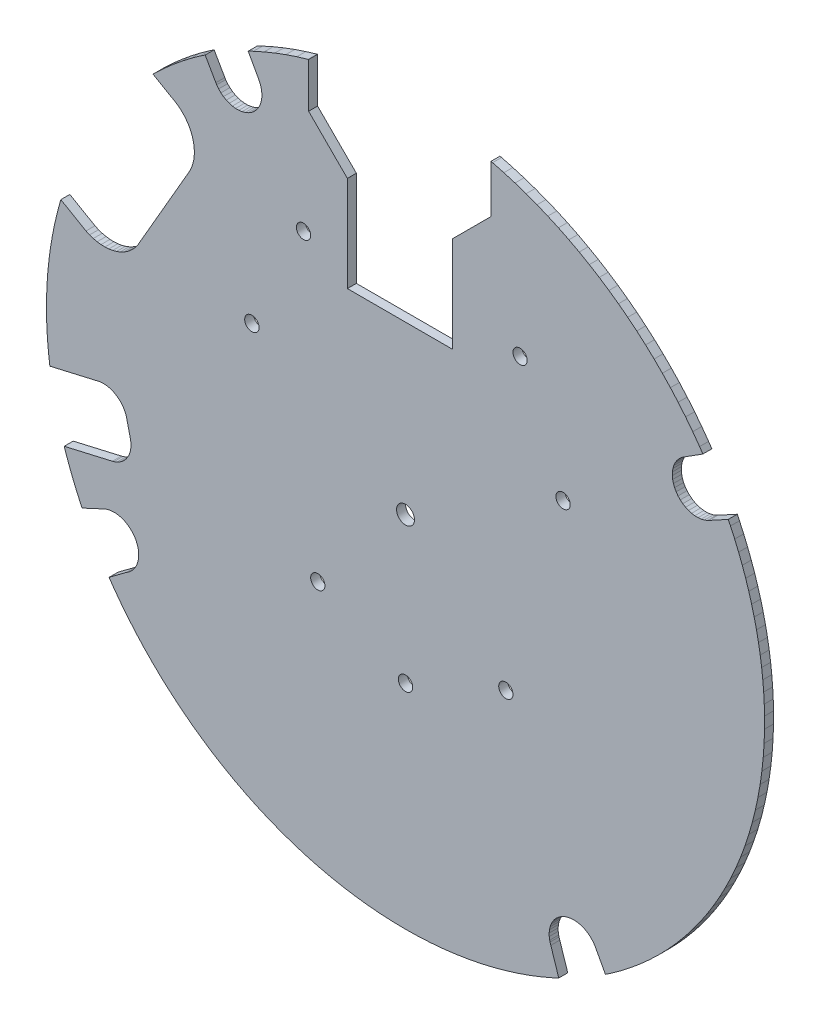
SolidWorks part; units mm, degrees
ref_plane "Płaszczyzna przednia" through (0, 0, 0) normal (0, 0, 1) x (1, 0, 0)
ref_plane "Płaszczyzna górna" through (0, 0, 0) normal (0, 1, 0) x (1, 0, 0)
ref_plane "Płaszczyzna prawa" through (0, 0, 0) normal (1, 0, 0) x (0, 0, -1)
sketch "Model" plane through (0, 0, 0) normal (0, 0, 1) x (1, 0, 0)
  line L0 (19.0436, 77.7128) -> (19.4018, 77.6295)
  line L1 (19.0436, 77.7128) -> (19.0437, 67.0537)
  line L2 (10.4176, 58.4277) -> (19.0437, 67.0537)
  line L3 (10.4176, 37.1511) -> (10.4176, 58.4277)
  line L4 (-12.9504, 37.1511) -> (10.4176, 37.1511)
  line L5 (-12.9504, 58.4177) -> (-12.9504, 37.1511)
  line L6 (-12.9603, 58.4177) -> (-12.9504, 58.4177)
  line L7 (-21.5964, 67.0537) -> (-12.9603, 58.4177)
  line L8 (-21.5964, 77.0457) -> (-21.5964, 67.0537)
  line L9 (-21.7211, 77.0127) -> (-21.5964, 77.0457)
  line L10 (-24.2112, 76.2665) -> (-21.7211, 77.0127)
  line L11 (-26.6758, 75.4398) -> (-24.2112, 76.2665)
  line L12 (-29.1122, 74.5335) -> (-26.6758, 75.4398)
  line L13 (-31.5179, 73.5485) -> (-29.1122, 74.5335)
  line L14 (-33.8903, 72.4859) -> (-31.5179, 73.5485)
  line L15 (-35.0587, 71.9164) -> (-33.8903, 72.4859)
  line L16 (-35.0587, 71.9164) -> (-32.6895, 67.6043)
  line L17 (-32.6895, 67.6043) -> (-32.532, 67.296)
  line L18 (-32.532, 67.296) -> (-32.2769, 66.6533)
  line L19 (-32.2769, 66.6533) -> (-32.1045, 65.9836)
  line L20 (-32.1045, 65.9836) -> (-32.0176, 65.2976)
  line L21 (-32.0176, 65.2976) -> (-32.0067, 64.9519)
  line L22 (-32.0185, 64.5922) -> (-32.0067, 64.9519)
  line L23 (-32.1126, 63.8789) -> (-32.0185, 64.5922)
  line L24 (-32.299, 63.184) -> (-32.1126, 63.8789)
  line L25 (-32.5747, 62.5194) -> (-32.299, 63.184)
  line L26 (-32.9348, 61.8965) -> (-32.5747, 62.5194)
  line L27 (-33.3733, 61.3261) -> (-32.9348, 61.8965)
  line L28 (-33.8826, 60.8179) -> (-33.3733, 61.3261)
  line L29 (-34.4539, 60.3805) -> (-33.8826, 60.8179)
  line L30 (-35.0775, 60.0217) -> (-34.4539, 60.3805)
  line L31 (-35.7426, 59.7473) -> (-35.0775, 60.0217)
  line L32 (-36.4379, 59.5623) -> (-35.7426, 59.7473)
  line L33 (-37.1514, 59.4697) -> (-36.4379, 59.5623)
  line L34 (-37.8709, 59.4712) -> (-37.1514, 59.4697)
  line L35 (-38.584, 59.5666) -> (-37.8709, 59.4712)
  line L36 (-39.2785, 59.7545) -> (-38.584, 59.5666)
  line L37 (-39.9425, 60.0315) -> (-39.2785, 59.7545)
  line L38 (-40.5646, 60.393) -> (-39.9425, 60.0315)
  line L39 (-41.1342, 60.8326) -> (-40.5646, 60.393)
  line L40 (-41.6414, 61.3429) -> (-41.1342, 60.8326)
  line L41 (-42.0775, 61.9151) -> (-41.6414, 61.3429)
  line L42 (-42.2666, 62.2214) -> (-42.0775, 61.9151)
  line L43 (-44.6488, 66.3808) -> (-42.2666, 62.2214)
  line L44 (-45.7359, 65.6581) -> (-44.6488, 66.3808)
  line L45 (-47.8425, 64.1394) -> (-45.7359, 65.6581)
  line L46 (-49.8986, 62.5531) -> (-47.8425, 64.1394)
  line L47 (-51.9022, 60.9009) -> (-49.8986, 62.5531)
  line L48 (-53.8511, 59.1846) -> (-51.9022, 60.9009)
  line L49 (-55.7433, 57.406) -> (-53.8511, 59.1846)
  line L50 (-56.2765, 56.8712) -> (-55.7433, 57.406)
  line L51 (-56.2765, 56.8712) -> (-51.5136, 54.1214)
  line L52 (-51.5136, 54.1214) -> (-51.1354, 53.903)
  line L53 (-51.1354, 53.903) -> (-50.4254, 53.3942)
  line L54 (-50.4254, 53.3942) -> (-49.7687, 52.8183)
  line L55 (-49.7687, 52.8183) -> (-49.1716, 52.1808)
  line L56 (-49.1716, 52.1808) -> (-48.6398, 51.4878)
  line L57 (-48.6398, 51.4878) -> (-48.1786, 50.746)
  line L58 (-48.1786, 50.746) -> (-47.7923, 49.9626)
  line L59 (-47.7923, 49.9626) -> (-47.4846, 49.1452)
  line L60 (-47.4846, 49.1452) -> (-47.2585, 48.3014)
  line L61 (-47.2585, 48.3014) -> (-47.1162, 47.4396)
  line L62 (-47.1162, 47.4396) -> (-47.0591, 46.568)
  line L63 (-47.0877, 45.695) -> (-47.0591, 46.568)
  line L64 (-47.2017, 44.829) -> (-47.0877, 45.695)
  line L65 (-47.4, 43.9784) -> (-47.2017, 44.829)
  line L66 (-47.6808, 43.1512) -> (-47.4, 43.9784)
  line L67 (-48.0413, 42.3556) -> (-47.6808, 43.1512)
  line L68 (-48.2597, 41.9774) -> (-48.0413, 42.3556)
  line L69 (-59.4357, 22.62) -> (-48.2597, 41.9774)
  line L70 (-59.654, 22.2418) -> (-59.4357, 22.62)
  line L71 (-60.1628, 21.5318) -> (-59.654, 22.2418)
  line L72 (-60.7387, 20.8751) -> (-60.1628, 21.5318)
  line L73 (-61.3762, 20.278) -> (-60.7387, 20.8751)
  line L74 (-62.0692, 19.7462) -> (-61.3762, 20.278)
  line L75 (-62.811, 19.285) -> (-62.0692, 19.7462)
  line L76 (-63.5944, 18.8986) -> (-62.811, 19.285)
  line L77 (-64.4119, 18.591) -> (-63.5944, 18.8986)
  line L78 (-65.2556, 18.3649) -> (-64.4119, 18.591)
  line L79 (-66.1174, 18.2226) -> (-65.2556, 18.3649)
  line L80 (-66.989, 18.1655) -> (-66.1174, 18.2226)
  line L81 (-67.862, 18.1941) -> (-66.989, 18.1655)
  line L82 (-68.728, 18.3081) -> (-67.862, 18.1941)
  line L83 (-69.5787, 18.5064) -> (-68.728, 18.3081)
  line L84 (-70.4058, 18.7872) -> (-69.5787, 18.5064)
  line L85 (-71.2014, 19.1477) -> (-70.4058, 18.7872)
  line L86 (-71.5796, 19.366) -> (-71.2014, 19.1477)
  line L87 (-76.8174, 22.3901) -> (-71.5796, 19.366)
  line L88 (-76.8834, 22.1744) -> (-76.8174, 22.3901)
  line L89 (-77.5625, 19.6678) -> (-76.8834, 22.1744)
  line L90 (-78.1599, 17.1405) -> (-77.5625, 19.6678)
  line L91 (-78.6749, 14.5952) -> (-78.1599, 17.1405)
  line L92 (-79.1071, 12.0345) -> (-78.6749, 14.5952)
  line L93 (-79.456, 9.4611) -> (-79.1071, 12.0345)
  line L94 (-79.7211, 6.8778) -> (-79.456, 9.4611)
  line L95 (-79.9023, 4.2872) -> (-79.7211, 6.8778)
  line L96 (-79.9994, 1.692) -> (-79.9023, 4.2872)
  line L97 (-80.0121, -0.9048) -> (-79.9994, 1.692)
  line L98 (-80.0121, -0.9048) -> (-79.9407, -3.5008)
  line L99 (-79.9407, -3.5008) -> (-79.7849, -6.093)
  line L100 (-79.7849, -6.093) -> (-79.5452, -8.6789)
  line L101 (-79.5452, -8.6789) -> (-79.257, -10.9741)
  line L102 (-79.257, -10.9741) -> (-68.5352, -8.4988)
  line L103 (-68.5352, -8.4988) -> (-68.1939, -8.42)
  line L104 (-68.1939, -8.42) -> (-67.4966, -8.3528)
  line L105 (-67.4966, -8.3528) -> (-66.7965, -8.3773)
  line L106 (-66.7965, -8.3773) -> (-66.1056, -8.4929)
  line L107 (-66.1056, -8.4929) -> (-65.4357, -8.6977)
  line L108 (-65.4357, -8.6977) -> (-64.7982, -8.9882)
  line L109 (-64.7982, -8.9882) -> (-64.2042, -9.3594)
  line L110 (-64.2042, -9.3594) -> (-63.6636, -9.805)
  line L111 (-63.6636, -9.805) -> (-63.1859, -10.3174)
  line L112 (-63.1859, -10.3174) -> (-62.7791, -10.8877)
  line L113 (-62.7791, -10.8877) -> (-62.4502, -11.5062)
  line L114 (-62.4502, -11.5062) -> (-62.2049, -12.1624)
  line L115 (-62.2049, -12.1624) -> (-62.1261, -12.5037)
  line L116 (-62.1261, -12.5037) -> (-61.3306, -15.949)
  line L117 (-61.3306, -15.949) -> (-61.2518, -16.2903)
  line L118 (-61.2518, -16.2903) -> (-61.1847, -16.9876)
  line L119 (-61.2092, -17.6877) -> (-61.1847, -16.9876)
  line L120 (-61.3248, -18.3787) -> (-61.2092, -17.6877)
  line L121 (-61.5296, -19.0486) -> (-61.3248, -18.3787)
  line L122 (-61.8201, -19.686) -> (-61.5296, -19.0486)
  line L123 (-62.1913, -20.2801) -> (-61.8201, -19.686)
  line L124 (-62.6369, -20.8206) -> (-62.1913, -20.2801)
  line L125 (-63.1492, -21.2984) -> (-62.6369, -20.8206)
  line L126 (-63.7196, -21.7052) -> (-63.1492, -21.2984)
  line L127 (-64.3381, -22.0341) -> (-63.7196, -21.7052)
  line L128 (-64.9942, -22.2794) -> (-64.3381, -22.0341)
  line L129 (-65.3355, -22.3582) -> (-64.9942, -22.2794)
  line L130 (-76.0559, -24.8332) -> (-65.3355, -22.3582)
  line L131 (-76.0559, -24.8332) -> (-75.5463, -26.3728)
  line L132 (-75.5463, -26.3728) -> (-74.6507, -28.8104)
  line L133 (-74.6507, -28.8104) -> (-73.6765, -31.2177)
  line L134 (-73.6765, -31.2177) -> (-72.6246, -33.5921)
  line L135 (-72.6246, -33.5921) -> (-72.0605, -34.7616)
  line L136 (-72.0605, -34.7616) -> (-67.6679, -32.7251)
  line L137 (-67.6679, -32.7251) -> (-67.3499, -32.5578)
  line L138 (-67.3499, -32.5578) -> (-66.6865, -32.2878)
  line L139 (-66.6865, -32.2878) -> (-65.9935, -32.1064)
  line L140 (-65.9935, -32.1064) -> (-65.2829, -32.0167)
  line L141 (-65.2829, -32.0167) -> (-64.5666, -32.0203)
  line L142 (-64.5666, -32.0203) -> (-63.8569, -32.117)
  line L143 (-63.8569, -32.117) -> (-63.1658, -32.3052)
  line L144 (-63.1658, -32.3052) -> (-62.505, -32.5818)
  line L145 (-62.505, -32.5818) -> (-61.8859, -32.942)
  line L146 (-61.8859, -32.942) -> (-61.3189, -33.3797)
  line L147 (-61.3189, -33.3797) -> (-60.8136, -33.8874)
  line L148 (-60.8136, -33.8874) -> (-60.3788, -34.4566)
  line L149 (-60.3788, -34.4566) -> (-60.0216, -35.0775)
  line L150 (-60.0216, -35.0775) -> (-59.7483, -35.7396)
  line L151 (-59.7483, -35.7396) -> (-59.5635, -36.4317)
  line L152 (-59.5635, -36.4317) -> (-59.4703, -37.1419)
  line L153 (-59.4703, -37.1419) -> (-59.4586, -37.5)
  line L154 (-59.4706, -37.8616) -> (-59.4586, -37.5)
  line L155 (-59.5656, -38.5787) -> (-59.4706, -37.8616)
  line L156 (-59.754, -39.277) -> (-59.5656, -38.5787)
  line L157 (-60.0325, -39.9445) -> (-59.754, -39.277)
  line L158 (-60.3963, -40.5696) -> (-60.0325, -39.9445)
  line L159 (-60.8391, -41.1416) -> (-60.3963, -40.5696)
  line L160 (-61.3532, -41.6503) -> (-60.8391, -41.1416)
  line L161 (-61.9297, -42.0872) -> (-61.3532, -41.6503)
  line L162 (-62.2382, -42.2762) -> (-61.9297, -42.0872)
  line L163 (-66.0571, -45.1277) -> (-62.2382, -42.2762)
  line L164 (-66.0571, -45.1277) -> (-65.2615, -46.3034)
  line L165 (-65.2615, -46.3034) -> (-63.5862, -48.5784)
  line L166 (-63.5862, -48.5784) -> (-61.8317, -50.7929)
  line L167 (-61.8317, -50.7929) -> (-60, -52.944)
  line L168 (-60, -52.944) -> (-58.0936, -55.0292)
  line L169 (-58.0936, -55.0292) -> (-56.1147, -57.0457)
  line L170 (-56.1147, -57.0457) -> (-54.0659, -58.9911)
  line L171 (-54.0659, -58.9911) -> (-51.9496, -60.863)
  line L172 (-51.9496, -60.863) -> (-49.7687, -62.659)
  line L173 (-49.7687, -62.659) -> (-47.5256, -64.3769)
  line L174 (-47.5256, -64.3769) -> (-45.2233, -66.0146)
  line L175 (-45.2233, -66.0146) -> (-42.8647, -67.5699)
  line L176 (-42.8647, -67.5699) -> (-40.4526, -69.041)
  line L177 (-40.4526, -69.041) -> (-37.9901, -70.426)
  line L178 (-37.9901, -70.426) -> (-35.4802, -71.7233)
  line L179 (-35.4802, -71.7233) -> (-32.9261, -72.9311)
  line L180 (-32.9261, -72.9311) -> (-30.3309, -74.048)
  line L181 (-30.3309, -74.048) -> (-27.6979, -75.0726)
  line L182 (-27.6979, -75.0726) -> (-25.0304, -76.0036)
  line L183 (-25.0304, -76.0036) -> (-22.3317, -76.8399)
  line L184 (-22.3317, -76.8399) -> (-19.6051, -77.5804)
  line L185 (-19.6051, -77.5804) -> (-16.8541, -78.2241)
  line L186 (-16.8541, -78.2241) -> (-14.0821, -78.7703)
  line L187 (-14.0821, -78.7703) -> (-11.2926, -79.2184)
  line L188 (-11.2926, -79.2184) -> (-8.4889, -79.5676)
  line L189 (-8.4889, -79.5676) -> (-5.6747, -79.8177)
  line L190 (-5.6747, -79.8177) -> (-2.8534, -79.9683)
  line L191 (-2.8534, -79.9683) -> (-0.0286, -80.0192)
  line L192 (-0.0286, -80.0192) -> (2.7963, -79.9703)
  line L193 (2.7963, -79.9703) -> (5.6177, -79.8218)
  line L194 (5.6177, -79.8218) -> (8.4321, -79.5737)
  line L195 (8.4321, -79.5737) -> (11.236, -79.2264)
  line L196 (11.236, -79.2264) -> (14.0259, -78.7804)
  line L197 (14.0259, -78.7804) -> (16.7983, -78.2361)
  line L198 (16.7983, -78.2361) -> (19.5497, -77.5943)
  line L199 (19.5497, -77.5943) -> (22.2768, -76.8558)
  line L200 (22.2768, -76.8558) -> (24.9761, -76.0215)
  line L201 (24.9761, -76.0215) -> (27.6443, -75.0924)
  line L202 (27.6443, -75.0924) -> (30.278, -74.0697)
  line L203 (30.278, -74.0697) -> (32.8739, -72.9546)
  line L204 (32.8739, -72.9546) -> (34.1514, -72.3516)
  line L205 (32.3764, -66.9332) -> (34.1514, -72.3516)
  line L206 (32.2007, -66.3987) -> (32.3764, -66.9332)
  line L207 (32.1227, -66.0746) -> (32.2007, -66.3987)
  line L208 (32.0263, -65.4152) -> (32.1227, -66.0746)
  line L209 (32.0105, -64.749) -> (32.0263, -65.4152)
  line L210 (32.0105, -64.749) -> (32.0754, -64.0858)
  line L211 (32.0754, -64.0858) -> (32.2202, -63.4354)
  line L212 (32.2202, -63.4354) -> (32.4427, -62.8073)
  line L213 (32.4427, -62.8073) -> (32.7396, -62.2107)
  line L214 (32.7396, -62.2107) -> (33.1065, -61.6544)
  line L215 (33.1065, -61.6544) -> (33.5381, -61.1467)
  line L216 (33.5381, -61.1467) -> (34.028, -60.695)
  line L217 (34.028, -60.695) -> (34.569, -60.3059)
  line L218 (34.569, -60.3059) -> (35.1531, -59.9852)
  line L219 (35.1531, -59.9852) -> (35.7717, -59.7376)
  line L220 (35.7717, -59.7376) -> (36.4158, -59.5667)
  line L221 (36.4158, -59.5667) -> (37.0759, -59.475)
  line L222 (37.0759, -59.475) -> (37.7421, -59.464)
  line L223 (37.7421, -59.464) -> (38.4049, -59.5337)
  line L224 (38.4049, -59.5337) -> (39.0543, -59.6831)
  line L225 (39.0543, -59.6831) -> (39.6808, -59.9101)
  line L226 (39.6808, -59.9101) -> (40.2752, -60.2112)
  line L227 (40.2752, -60.2112) -> (40.8288, -60.5821)
  line L228 (40.8288, -60.5821) -> (41.3334, -61.0173)
  line L229 (41.3334, -61.0173) -> (41.7816, -61.5105)
  line L230 (41.7816, -61.5105) -> (42.1668, -62.0542)
  line L231 (42.1668, -62.0542) -> (42.334, -62.3426)
  line L232 (42.334, -62.3426) -> (44.5493, -66.4474)
  line L233 (44.5493, -66.4474) -> (45.7221, -65.6698)
  line L234 (45.7221, -65.6698) -> (47.9923, -64.0295)
  line L235 (47.9923, -64.0295) -> (50.2037, -62.3107)
  line L236 (50.2037, -62.3107) -> (52.3536, -60.5156)
  line L237 (52.3536, -60.5156) -> (54.4394, -58.6463)
  line L238 (54.4394, -58.6463) -> (56.4584, -56.7052)
  line L239 (56.4584, -56.7052) -> (58.4083, -54.6947)
  line L240 (58.4083, -54.6947) -> (60.2867, -52.6171)
  line L241 (60.2867, -52.6171) -> (62.0911, -50.475)
  line L242 (62.0911, -50.475) -> (63.8195, -48.2711)
  line L243 (63.8195, -48.2711) -> (65.4698, -46.0081)
  line L244 (65.4698, -46.0081) -> (67.0398, -43.6887)
  line L245 (67.0398, -43.6887) -> (68.5277, -41.3158)
  line L246 (68.5277, -41.3158) -> (69.9316, -38.8923)
  line L247 (69.9316, -38.8923) -> (71.2498, -36.4211)
  line L248 (71.2498, -36.4211) -> (72.4808, -33.9053)
  line L249 (72.4808, -33.9053) -> (73.623, -31.348)
  line L250 (73.623, -31.348) -> (74.6749, -28.7523)
  line L251 (74.6749, -28.7523) -> (75.6354, -26.1213)
  line L252 (75.6354, -26.1213) -> (76.5032, -23.4583)
  line L253 (76.5032, -23.4583) -> (77.2773, -20.7666)
  line L254 (77.2773, -20.7666) -> (77.9567, -18.0495)
  line L255 (77.9567, -18.0495) -> (78.5407, -15.3102)
  line L256 (78.5407, -15.3102) -> (79.0284, -12.5522)
  line L257 (79.0284, -12.5522) -> (79.4192, -9.7788)
  line L258 (79.4192, -9.7788) -> (79.7128, -6.9934)
  line L259 (79.7128, -6.9934) -> (79.9087, -4.1995)
  line L260 (79.9087, -4.1995) -> (80.0067, -1.4004)
  line L261 (80.0067, -1.4004) -> (80.0067, 0)
  line L262 (80.0067, 0) -> (80.0067, 1.1336)
  line L263 (79.9425, 3.4) -> (80.0067, 1.1336)
  line L264 (79.8141, 5.6637) -> (79.9425, 3.4)
  line L265 (79.6216, 7.9228) -> (79.8141, 5.6637)
  line L266 (79.3651, 10.1755) -> (79.6216, 7.9228)
  line L267 (79.0449, 12.4201) -> (79.3651, 10.1755)
  line L268 (78.6613, 14.6547) -> (79.0449, 12.4201)
  line L269 (78.2145, 16.8775) -> (78.6613, 14.6547)
  line L270 (77.7049, 19.0868) -> (78.2145, 16.8775)
  line L271 (77.1329, 21.2808) -> (77.7049, 19.0868)
  line L272 (76.499, 23.4576) -> (77.1329, 21.2808)
  line L273 (75.8037, 25.6157) -> (76.499, 23.4576)
  line L274 (75.0475, 27.7531) -> (75.8037, 25.6157)
  line L275 (74.231, 29.8683) -> (75.0475, 27.7531)
  line L276 (73.355, 31.9595) -> (74.231, 29.8683)
  line L277 (72.42, 34.0251) -> (73.355, 31.9595)
  line L278 (71.9235, 35.0442) -> (72.42, 34.0251)
  line L279 (67.5882, 32.6807) -> (71.9235, 35.0442)
  line L280 (67.2669, 32.5184) -> (67.5882, 32.6807)
  line L281 (66.5967, 32.2587) -> (67.2669, 32.5184)
  line L282 (65.8983, 32.0889) -> (66.5967, 32.2587)
  line L283 (65.1837, 32.0116) -> (65.8983, 32.0889)
  line L284 (64.4651, 32.0283) -> (65.1837, 32.0116)
  line L285 (63.7549, 32.1387) -> (64.4651, 32.0283)
  line L286 (63.0651, 32.3409) -> (63.7549, 32.1387)
  line L287 (62.4077, 32.6314) -> (63.0651, 32.3409)
  line L288 (61.7938, 33.0053) -> (62.4077, 32.6314)
  line L289 (61.234, 33.4561) -> (61.7938, 33.0053)
  line L290 (60.7378, 33.9762) -> (61.234, 33.4561)
  line L291 (60.3138, 34.5565) -> (60.7378, 33.9762)
  line L292 (59.9692, 35.1873) -> (60.3138, 34.5565)
  line L293 (59.7099, 35.8577) -> (59.9692, 35.1873)
  line L294 (59.5403, 36.5561) -> (59.7099, 35.8577)
  line L295 (59.4634, 37.2708) -> (59.5403, 36.5561)
  line L296 (59.4634, 37.2708) -> (59.4805, 37.9893)
  line L297 (59.4805, 37.9893) -> (59.5912, 38.6995)
  line L298 (59.5912, 38.6995) -> (59.7937, 39.3892)
  line L299 (59.7937, 39.3892) -> (60.0845, 40.0465)
  line L300 (60.0845, 40.0465) -> (60.4587, 40.6602)
  line L301 (60.4587, 40.6602) -> (60.9097, 41.2198)
  line L302 (60.9097, 41.2198) -> (61.43, 41.7157)
  line L303 (61.43, 41.7157) -> (62.0106, 42.1395)
  line L304 (62.0106, 42.1395) -> (62.3204, 42.3219)
  line L305 (62.3204, 42.3219) -> (66.2604, 44.8278)
  line L306 (65.5338, 45.9139) -> (66.2604, 44.8278)
  line L307 (64.0078, 48.0184) -> (65.5338, 45.9139)
  line L308 (62.4143, 50.0722) -> (64.0078, 48.0184)
  line L309 (60.7549, 52.0732) -> (62.4143, 50.0722)
  line L310 (59.0313, 54.0192) -> (60.7549, 52.0732)
  line L311 (57.2455, 55.9082) -> (59.0313, 54.0192)
  line L312 (55.3992, 57.7382) -> (57.2455, 55.9082)
  line L313 (53.4945, 59.5072) -> (55.3992, 57.7382)
  line L314 (51.5333, 61.2135) -> (53.4945, 59.5072)
  line L315 (49.5177, 62.8551) -> (51.5333, 61.2135)
  line L316 (47.4499, 64.4304) -> (49.5177, 62.8551)
  line L317 (45.3319, 65.9377) -> (47.4499, 64.4304)
  line L318 (43.1662, 67.3754) -> (45.3319, 65.9377)
  line L319 (40.9549, 68.742) -> (43.1662, 67.3754)
  line L320 (38.7003, 70.0361) -> (40.9549, 68.742)
  line L321 (36.4049, 71.2562) -> (38.7003, 70.0361)
  line L322 (34.0711, 72.4011) -> (36.4049, 71.2562)
  line L323 (31.7014, 73.4697) -> (34.0711, 72.4011)
  line L324 (29.2981, 74.4606) -> (31.7014, 73.4697)
  line L325 (26.864, 75.373) -> (29.2981, 74.4606)
  line L326 (24.4015, 76.2059) -> (26.864, 75.373)
  line L327 (21.9132, 76.9583) -> (24.4015, 76.2059)
  line L328 (19.4018, 77.6295) -> (21.9132, 76.9583)
  circle A0 centre (9.6556, -72.0924) radius 0.4
  circle A1 centre (9.6556, -67.0923) radius 0.4
  circle A2 centre (-28.5984, -30.6643) radius 0.635
  circle A3 centre (-40.5984, -30.6643) radius 0.635
  circle A4 centre (-37.5984, -28.7043) radius 0.51
  circle A5 centre (-34.5984, -28.7043) radius 0.51
  circle A6 centre (-31.5984, -28.7043) radius 0.51
  circle A7 centre (50.2246, -41.3563) radius 0.51
  circle A8 centre (50.2246, -38.3563) radius 0.51
  circle A9 centre (50.2246, -35.3564) radius 0.51
  circle A10 centre (48.2647, -32.3563) radius 0.635
  circle A11 centre (48.2647, -44.3564) radius 0.635
  circle A12 centre (38.0456, -18.7983) radius 0.51
  circle A13 centre (35.0456, -18.7983) radius 0.51
  circle A14 centre (32.0456, -20.7583) radius 0.635
  circle A15 centre (44.0456, -20.7583) radius 0.635
  circle A16 centre (41.0456, -18.7983) radius 0.51
  circle A17 centre (-34.2483, 36.5737) radius 0.51
  circle A18 centre (-37.2483, 36.5737) radius 0.51
  circle A19 centre (-31.2483, 36.5737) radius 0.51
  circle A20 centre (-28.2483, 34.6137) radius 0.635
  circle A21 centre (-40.2483, 34.6137) radius 0.635
  circle A22 centre (-34.2483, 44.9557) radius 0.51
  circle A23 centre (-37.2483, 44.9557) radius 0.51
  circle A24 centre (-28.2483, 42.9957) radius 0.635
  circle A25 centre (-40.2483, 42.9957) radius 0.635
  circle A26 centre (-31.2483, 44.9557) radius 0.51
  circle A27 centre (38.0936, -9.1463) radius 0.51
  circle A28 centre (41.0936, -9.1463) radius 0.51
  circle A29 centre (44.0937, -11.1063) radius 0.635
  circle A30 centre (32.0936, -11.1063) radius 0.635
  circle A31 centre (35.0937, -9.1463) radius 0.51
  circle A32 centre (-65.7483, 0.2516) radius 2.275
  circle A33 centre (-72.9484, 0.2516) radius 2.275
  circle A34 centre (-1.4203, -65.4063) radius 2.275
  circle A35 centre (-1.4203, -72.6064) radius 2.275
  circle A36 centre (-55.3783, -16.5123) radius 0.45
  circle A37 centre (-55.3783, -19.0523) radius 0.45
  circle A38 centre (-55.3783, -17.7823) radius 0.45
  circle A39 centre (41.1416, 9.3957) radius 0.45
  circle A40 centre (41.1416, 11.9357) radius 0.45
  circle A41 centre (41.1416, 10.6657) radius 0.45
  circle A42 centre (-7.3723, -56.1363) radius 0.45
  circle A43 centre (-7.3723, -57.4063) radius 0.45
  circle A44 centre (-7.3723, -54.8663) radius 0.45
  circle A45 centre (24.2606, 12.8306) radius 0.381
  circle A46 centre (26.8006, 12.8306) radius 0.381
  circle A47 centre (26.8006, 33.1506) radius 0.381
  circle A48 centre (-21.4594, 38.2306) radius 0.381
  circle A49 centre (-23.9994, 38.2306) radius 0.381
  circle A50 centre (26.8006, 38.2306) radius 0.381
  circle A51 centre (24.2606, 38.2306) radius 0.381
  circle A52 centre (21.0856, 15.3706) radius 0.381
  circle A53 centre (-21.4594, 30.6106) radius 0.381
  circle A54 centre (21.0856, 2.6706) radius 0.381
  circle A55 centre (21.0856, 5.2106) radius 0.381
  circle A56 centre (21.0856, 7.7506) radius 0.381
  circle A57 centre (21.0856, 10.2906) radius 0.381
  circle A58 centre (21.0856, 12.8306) radius 0.381
  circle A59 centre (24.2606, -17.6494) radius 0.381
  circle A60 centre (26.8006, -17.6494) radius 0.381
  circle A61 centre (24.2606, -15.1094) radius 0.381
  circle A62 centre (26.8006, -15.1094) radius 0.381
  circle A63 centre (24.2606, -12.5694) radius 0.381
  circle A64 centre (26.8006, -12.5694) radius 0.381
  circle A65 centre (24.2606, -10.0294) radius 0.381
  circle A66 centre (26.8006, -10.0294) radius 0.381
  circle A67 centre (24.2606, -7.4894) radius 0.381
  circle A68 centre (26.8006, -7.4894) radius 0.381
  circle A69 centre (24.2606, -4.9494) radius 0.381
  circle A70 centre (26.8006, -4.9494) radius 0.381
  circle A71 centre (24.2606, -2.4094) radius 0.381
  circle A72 centre (26.8006, -2.4094) radius 0.381
  circle A73 centre (24.2606, 0.1306) radius 0.381
  circle A74 centre (26.8006, 0.1306) radius 0.381
  circle A75 centre (24.2606, 2.6706) radius 0.381
  circle A76 centre (26.8006, 2.6706) radius 0.381
  circle A77 centre (24.2606, 5.2106) radius 0.381
  circle A78 centre (26.8006, 5.2106) radius 0.381
  circle A79 centre (24.2606, 7.7506) radius 0.381
  circle A80 centre (26.8006, 7.7506) radius 0.381
  circle A81 centre (24.2606, 10.2906) radius 0.381
  circle A82 centre (26.8006, 10.2906) radius 0.381
  circle A83 centre (24.2606, 15.3706) radius 0.381
  circle A84 centre (26.8006, 15.3706) radius 0.381
  circle A85 centre (24.2606, 17.9106) radius 0.381
  circle A86 centre (26.8006, 17.9106) radius 0.381
  circle A87 centre (24.2606, 20.4506) radius 0.381
  circle A88 centre (26.8006, 20.4506) radius 0.381
  circle A89 centre (24.2606, 22.9906) radius 0.381
  circle A90 centre (26.8006, 22.9906) radius 0.381
  circle A91 centre (26.8006, 25.5306) radius 0.381
  circle A92 centre (24.2606, 28.0706) radius 0.381
  circle A93 centre (26.8006, 28.0706) radius 0.381
  circle A94 centre (24.2606, 30.6106) radius 0.381
  circle A95 centre (26.8006, 30.6106) radius 0.381
  circle A96 centre (24.2606, 33.1506) radius 0.381
  circle A97 centre (24.2606, 35.6906) radius 0.381
  circle A98 centre (26.8006, 35.6906) radius 0.381
  circle A99 centre (-23.9994, -17.6494) radius 0.381
  circle A100 centre (-21.4594, -17.6494) radius 0.381
  circle A101 centre (-23.9994, -15.1094) radius 0.381
  circle A102 centre (-21.4594, -15.1094) radius 0.381
  circle A103 centre (-23.9994, -12.5694) radius 0.381
  circle A104 centre (-21.4594, -12.5694) radius 0.381
  circle A105 centre (-23.9994, -10.0294) radius 0.381
  circle A106 centre (-21.4594, -10.0294) radius 0.381
  circle A107 centre (-23.9994, -7.4894) radius 0.381
  circle A108 centre (-21.4594, -7.4894) radius 0.381
  circle A109 centre (-23.9994, -4.9494) radius 0.381
  circle A110 centre (-21.4594, -4.9494) radius 0.381
  circle A111 centre (-23.9994, -2.4094) radius 0.381
  circle A112 centre (-21.4594, -2.4094) radius 0.381
  circle A113 centre (-23.9994, 0.1306) radius 0.381
  circle A114 centre (-21.4594, 0.1306) radius 0.381
  circle A115 centre (-23.9994, 2.6706) radius 0.381
  circle A116 centre (-21.4594, 2.6706) radius 0.381
  circle A117 centre (-23.9994, 5.2106) radius 0.381
  circle A118 centre (-21.4594, 5.2106) radius 0.381
  circle A119 centre (-23.9994, 7.7506) radius 0.381
  circle A120 centre (-21.4594, 7.7506) radius 0.381
  circle A121 centre (-23.9994, 10.2906) radius 0.381
  circle A122 centre (-21.4594, 10.2906) radius 0.381
  circle A123 centre (-23.9994, 12.8306) radius 0.381
  circle A124 centre (-21.4594, 12.8306) radius 0.381
  circle A125 centre (-23.9994, 15.3706) radius 0.381
  circle A126 centre (-21.4594, 15.3706) radius 0.381
  circle A127 centre (-23.9994, 17.9106) radius 0.381
  circle A128 centre (-21.4594, 17.9106) radius 0.381
  circle A129 centre (-23.9994, 20.4506) radius 0.381
  circle A130 centre (-21.4594, 20.4506) radius 0.381
  circle A131 centre (-23.9994, 22.9906) radius 0.381
  circle A132 centre (-21.4594, 22.9906) radius 0.381
  circle A133 centre (-23.9994, 25.5306) radius 0.381
  circle A134 centre (-23.9994, 28.0706) radius 0.381
  circle A135 centre (-23.9994, 30.6106) radius 0.381
  circle A136 centre (-23.9994, 33.1506) radius 0.381
  circle A137 centre (-21.4594, 33.1506) radius 0.381
  circle A138 centre (-23.9994, 35.6906) radius 0.381
  circle A139 centre (-21.4594, 35.6906) radius 0.381
  circle A140 centre (-19.5544, -22.7294) radius 1.5875
  circle A141 centre (22.3556, -22.7294) radius 1.5875
  circle A142 centre (-22.7294, 43.3106) radius 1.5875
  circle A143 centre (25.5306, 43.3106) radius 1.5875
  circle A144 centre (-21.4594, 25.5306) radius 0.381
  circle A145 centre (-21.4594, 28.0706) radius 0.381
  circle A146 centre (24.2606, 25.5306) radius 0.381
  circle A147 centre (-29.4764, 56.5276) radius 0.0875
  circle A148 centre (-29.4764, 56.6151) radius 0.0437
  circle A149 centre (-29.4764, 56.4401) radius 0.0437
  circle A150 centre (-29.4764, 54.9276) radius 0.0875
  circle A151 centre (-29.4764, 55.0151) radius 0.0437
  circle A152 centre (-29.4764, 54.8401) radius 0.0437
  circle A153 centre (55.3657, 36.3197) radius 0.51
  circle A154 centre (55.3657, 38.8597) radius 0.51
  circle A155 centre (44.0797, 5.0056) radius 0.635
  circle A156 centre (56.0797, 5.0056) radius 0.635
  circle A157 centre (53.0797, 3.0457) radius 0.51
  circle A158 centre (50.0797, 3.0457) radius 0.51
  circle A159 centre (47.0797, 3.0457) radius 0.51
  circle A160 centre (-3.9163, -53.1544) radius 0.635
  circle A161 centre (8.0837, -53.1544) radius 0.635
  circle A162 centre (5.0836, -55.1144) radius 0.51
  circle A163 centre (2.0837, -55.1144) radius 0.51
  circle A164 centre (-0.9163, -55.1144) radius 0.51
  circle A165 centre (-30.6923, -55.1203) radius 0.51
  circle A166 centre (-33.6923, -55.1203) radius 0.51
  circle A167 centre (-27.6924, -55.1203) radius 0.51
  circle A168 centre (-24.6923, -53.1604) radius 0.635
  circle A169 centre (-36.6923, -53.1604) radius 0.635
  circle A170 centre (-46.2343, 12.1897) radius 0.5
  circle A171 centre (-48.7744, 12.1897) radius 0.5
  circle A172 centre (-33.5343, 12.1897) radius 0.5
  circle A173 centre (-36.0744, 12.1897) radius 0.5
  circle A174 centre (-46.2343, 22.6037) radius 0.5
  circle A175 centre (-48.7744, 22.6037) radius 0.5
  circle A176 centre (-34.3444, 27.9377) radius 0.51
  circle A177 centre (-37.3443, 27.9377) radius 0.51
  circle A178 centre (-40.3444, 25.9777) radius 0.635
  circle A179 centre (-28.3444, 25.9777) radius 0.635
  circle A180 centre (-31.3444, 27.9377) radius 0.51
  circle A181 centre (51.5556, 43.7657) radius 0.6
  circle A182 centre (48.0556, 43.7657) radius 0.6
  circle A183 centre (51.5556, 48.7657) radius 0.6
  circle A184 centre (48.0556, 48.7657) radius 0.6
  circle A185 centre (30.8516, 3.2997) radius 0.51
  circle A186 centre (30.8516, 0.7597) radius 0.51
  circle A187 centre (-66.8483, 10.9197) radius 0.4
  circle A188 centre (-71.8484, 10.9197) radius 0.4
  circle A189 centre (35.306, 15.24) radius 0.55
  circle A190 centre (35.306, 12.7) radius 0.55
  circle A191 centre (35.306, 10.16) radius 0.55
  circle A192 centre (39.6176, 3.5537) radius 0.55
  circle A193 centre (39.6176, -1.5263) radius 0.55
  circle A194 centre (39.6176, 1.0137) radius 0.55
  circle A195 centre (30.9816, 11.4277) radius 0.55
  circle A196 centre (30.9816, 8.8877) radius 0.55
  circle A197 centre (30.9816, 6.3477) radius 0.55
  circle A198 centre (-50.2983, 2.5377) radius 0.51
  circle A199 centre (-50.2983, 5.0777) radius 0.51
  circle A202 centre (19.0436, 77.7128) radius 0.25
  circle A205 centre (19.0437, 67.0537) radius 0.25
  circle A207 centre (10.4176, 58.4277) radius 0.25
  circle A209 centre (10.4176, 37.1511) radius 0.25
  circle A211 centre (-12.9504, 37.1511) radius 0.25
  circle A213 centre (-12.9504, 58.4177) radius 0.25
  circle A215 centre (-12.9603, 58.4177) radius 0.25
  circle A217 centre (-21.5964, 67.0537) radius 0.25
  circle A219 centre (-21.5964, 77.0457) radius 0.25
  circle A221 centre (-21.7211, 77.0127) radius 0.25
  circle A223 centre (-24.2112, 76.2665) radius 0.25
  circle A225 centre (-26.6758, 75.4398) radius 0.25
  circle A227 centre (-29.1122, 74.5335) radius 0.25
  circle A229 centre (-31.5179, 73.5485) radius 0.25
  circle A231 centre (-33.8903, 72.4859) radius 0.25
  circle A232 centre (-35.0587, 71.9164) radius 0.25
  circle A234 centre (-32.6895, 67.6043) radius 0.25
  circle A236 centre (-32.532, 67.296) radius 0.25
  circle A238 centre (-32.2769, 66.6533) radius 0.25
  circle A240 centre (-32.1045, 65.9836) radius 0.25
  circle A242 centre (-32.0176, 65.2976) radius 0.25
  circle A245 centre (-32.0067, 64.9519) radius 0.25
  circle A247 centre (-32.0185, 64.5922) radius 0.25
  circle A249 centre (-32.1126, 63.8789) radius 0.25
  circle A251 centre (-32.299, 63.184) radius 0.25
  circle A253 centre (-32.5747, 62.5194) radius 0.25
  circle A255 centre (-32.9348, 61.8965) radius 0.25
  circle A257 centre (-33.3733, 61.3261) radius 0.25
  circle A259 centre (-33.8826, 60.8179) radius 0.25
  circle A261 centre (-34.4539, 60.3805) radius 0.25
  circle A263 centre (-35.0775, 60.0217) radius 0.25
  circle A265 centre (-35.7426, 59.7473) radius 0.25
  circle A267 centre (-36.4379, 59.5623) radius 0.25
  circle A269 centre (-37.1514, 59.4697) radius 0.25
  circle A271 centre (-37.8709, 59.4712) radius 0.25
  circle A273 centre (-38.584, 59.5666) radius 0.25
  circle A275 centre (-39.2785, 59.7545) radius 0.25
  circle A277 centre (-39.9425, 60.0315) radius 0.25
  circle A279 centre (-40.5646, 60.393) radius 0.25
  circle A281 centre (-41.1342, 60.8326) radius 0.25
  circle A283 centre (-41.6414, 61.3429) radius 0.25
  circle A285 centre (-42.0775, 61.9151) radius 0.25
  circle A287 centre (-42.2666, 62.2214) radius 0.25
  circle A289 centre (-44.6488, 66.3808) radius 0.25
  circle A291 centre (-45.7359, 65.6581) radius 0.25
  circle A293 centre (-47.8425, 64.1394) radius 0.25
  circle A295 centre (-49.8986, 62.5531) radius 0.25
  circle A297 centre (-51.9022, 60.9009) radius 0.25
  circle A299 centre (-53.8511, 59.1846) radius 0.25
  circle A301 centre (-55.7433, 57.406) radius 0.25
  circle A302 centre (-56.2765, 56.8712) radius 0.25
  circle A306 centre (-51.5136, 54.1214) radius 0.25
  circle A308 centre (-51.1354, 53.903) radius 0.25
  circle A310 centre (-50.4254, 53.3942) radius 0.25
  circle A312 centre (-49.7687, 52.8183) radius 0.25
  circle A314 centre (-49.1716, 52.1808) radius 0.25
  circle A316 centre (-48.6398, 51.4878) radius 0.25
  circle A318 centre (-48.1786, 50.746) radius 0.25
  circle A320 centre (-47.7923, 49.9626) radius 0.25
  circle A322 centre (-47.4846, 49.1452) radius 0.25
  circle A324 centre (-47.2585, 48.3014) radius 0.25
  circle A326 centre (-47.1162, 47.4396) radius 0.25
  circle A329 centre (-47.0591, 46.568) radius 0.25
  circle A331 centre (-47.0877, 45.695) radius 0.25
  circle A333 centre (-47.2017, 44.829) radius 0.25
  circle A335 centre (-47.4, 43.9784) radius 0.25
  circle A337 centre (-47.6808, 43.1512) radius 0.25
  circle A339 centre (-48.0413, 42.3556) radius 0.25
  circle A341 centre (-48.2597, 41.9774) radius 0.25
  circle A345 centre (-59.4357, 22.62) radius 0.25
  circle A347 centre (-59.654, 22.2418) radius 0.25
  circle A349 centre (-60.1628, 21.5318) radius 0.25
  circle A351 centre (-60.7387, 20.8751) radius 0.25
  circle A353 centre (-61.3762, 20.278) radius 0.25
  circle A355 centre (-62.0692, 19.7462) radius 0.25
  circle A357 centre (-62.811, 19.285) radius 0.25
  circle A359 centre (-63.5944, 18.8986) radius 0.25
  circle A361 centre (-64.4119, 18.591) radius 0.25
  circle A363 centre (-65.2556, 18.3649) radius 0.25
  circle A365 centre (-66.1174, 18.2226) radius 0.25
  circle A367 centre (-66.989, 18.1655) radius 0.25
  circle A369 centre (-67.862, 18.1941) radius 0.25
  circle A371 centre (-68.728, 18.3081) radius 0.25
  circle A373 centre (-69.5787, 18.5064) radius 0.25
  circle A375 centre (-70.4058, 18.7872) radius 0.25
  circle A377 centre (-71.2014, 19.1477) radius 0.25
  circle A379 centre (-71.5796, 19.366) radius 0.25
  circle A381 centre (-76.8174, 22.3901) radius 0.25
  circle A383 centre (-76.8834, 22.1744) radius 0.25
  circle A385 centre (-77.5625, 19.6678) radius 0.25
  circle A387 centre (-78.1599, 17.1405) radius 0.25
  circle A389 centre (-78.6749, 14.5952) radius 0.25
  circle A391 centre (-79.1071, 12.0345) radius 0.25
  circle A393 centre (-79.456, 9.4611) radius 0.25
  circle A395 centre (-79.7211, 6.8778) radius 0.25
  circle A397 centre (-79.9023, 4.2872) radius 0.25
  circle A399 centre (-79.9994, 1.692) radius 0.25
  circle A400 centre (-80.0121, -0.9048) radius 0.25
  circle A402 centre (-79.9407, -3.5008) radius 0.25
  circle A404 centre (-79.7849, -6.093) radius 0.25
  circle A406 centre (-79.5452, -8.6789) radius 0.25
  circle A408 centre (-79.257, -10.9741) radius 0.25
  circle A410 centre (-68.5352, -8.4988) radius 0.25
  circle A412 centre (-68.1939, -8.42) radius 0.25
  circle A414 centre (-67.4966, -8.3528) radius 0.25
  circle A416 centre (-66.7965, -8.3773) radius 0.25
  circle A418 centre (-66.1056, -8.4929) radius 0.25
  circle A420 centre (-65.4357, -8.6977) radius 0.25
  circle A422 centre (-64.7982, -8.9882) radius 0.25
  circle A424 centre (-64.2042, -9.3594) radius 0.25
  circle A426 centre (-63.6636, -9.805) radius 0.25
  circle A428 centre (-63.1859, -10.3174) radius 0.25
  circle A430 centre (-62.7791, -10.8877) radius 0.25
  circle A432 centre (-62.4502, -11.5062) radius 0.25
  circle A434 centre (-62.2049, -12.1624) radius 0.25
  circle A438 centre (-62.1261, -12.5037) radius 0.25
  circle A440 centre (-61.3306, -15.949) radius 0.25
  circle A442 centre (-61.2518, -16.2903) radius 0.25
  circle A445 centre (-61.1847, -16.9876) radius 0.25
  circle A447 centre (-61.2092, -17.6877) radius 0.25
  circle A449 centre (-61.3248, -18.3787) radius 0.25
  circle A451 centre (-61.5296, -19.0486) radius 0.25
  circle A453 centre (-61.8201, -19.686) radius 0.25
  circle A455 centre (-62.1913, -20.2801) radius 0.25
  circle A457 centre (-62.6369, -20.8206) radius 0.25
  circle A459 centre (-63.1492, -21.2984) radius 0.25
  circle A461 centre (-63.7196, -21.7052) radius 0.25
  circle A463 centre (-64.3381, -22.0341) radius 0.25
  circle A465 centre (-64.9942, -22.2794) radius 0.25
  circle A469 centre (-65.3355, -22.3582) radius 0.25
  circle A470 centre (-76.0559, -24.8332) radius 0.25
  circle A472 centre (-75.5463, -26.3728) radius 0.25
  circle A474 centre (-74.6507, -28.8104) radius 0.25
  circle A476 centre (-73.6765, -31.2177) radius 0.25
  circle A478 centre (-72.6246, -33.5921) radius 0.25
  circle A480 centre (-72.0605, -34.7616) radius 0.25
  circle A482 centre (-67.6679, -32.7251) radius 0.25
  circle A484 centre (-67.3499, -32.5578) radius 0.25
  circle A486 centre (-66.6865, -32.2878) radius 0.25
  circle A488 centre (-65.9935, -32.1064) radius 0.25
  circle A490 centre (-65.2829, -32.0167) radius 0.25
  circle A492 centre (-64.5666, -32.0203) radius 0.25
  circle A494 centre (-63.8569, -32.117) radius 0.25
  circle A496 centre (-63.1658, -32.3052) radius 0.25
  circle A498 centre (-62.505, -32.5818) radius 0.25
  circle A500 centre (-61.8859, -32.942) radius 0.25
  circle A502 centre (-61.3189, -33.3797) radius 0.25
  circle A504 centre (-60.8136, -33.8874) radius 0.25
  circle A506 centre (-60.3788, -34.4566) radius 0.25
  circle A508 centre (-60.0216, -35.0775) radius 0.25
  circle A510 centre (-59.7483, -35.7396) radius 0.25
  circle A512 centre (-59.5635, -36.4317) radius 0.25
  circle A514 centre (-59.4703, -37.1419) radius 0.25
  circle A517 centre (-59.4586, -37.5) radius 0.25
  circle A519 centre (-59.4706, -37.8616) radius 0.25
  circle A521 centre (-59.5656, -38.5787) radius 0.25
  circle A523 centre (-59.754, -39.277) radius 0.25
  circle A525 centre (-60.0325, -39.9445) radius 0.25
  circle A527 centre (-60.3963, -40.5696) radius 0.25
  circle A529 centre (-60.8391, -41.1416) radius 0.25
  circle A531 centre (-61.3532, -41.6503) radius 0.25
  circle A533 centre (-61.9297, -42.0872) radius 0.25
  circle A535 centre (-62.2382, -42.2762) radius 0.25
  circle A536 centre (-66.0571, -45.1277) radius 0.25
  circle A538 centre (-65.2615, -46.3034) radius 0.25
  circle A540 centre (-63.5862, -48.5784) radius 0.25
  circle A542 centre (-61.8317, -50.7929) radius 0.25
  circle A544 centre (-60, -52.944) radius 0.25
  circle A546 centre (-58.0936, -55.0292) radius 0.25
  circle A548 centre (-56.1147, -57.0457) radius 0.25
  circle A550 centre (-54.0659, -58.9911) radius 0.25
  circle A552 centre (-51.9496, -60.863) radius 0.25
  circle A554 centre (-49.7687, -62.659) radius 0.25
  circle A556 centre (-47.5256, -64.3769) radius 0.25
  circle A558 centre (-45.2233, -66.0146) radius 0.25
  circle A560 centre (-42.8647, -67.5699) radius 0.25
  circle A562 centre (-40.4526, -69.041) radius 0.25
  circle A564 centre (-37.9901, -70.426) radius 0.25
  circle A566 centre (-35.4802, -71.7233) radius 0.25
  circle A568 centre (-32.9261, -72.9311) radius 0.25
  circle A570 centre (-30.3309, -74.048) radius 0.25
  circle A572 centre (-27.6979, -75.0726) radius 0.25
  circle A574 centre (-25.0304, -76.0036) radius 0.25
  circle A576 centre (-22.3317, -76.8399) radius 0.25
  circle A578 centre (-19.6051, -77.5804) radius 0.25
  circle A580 centre (-16.8541, -78.2241) radius 0.25
  circle A582 centre (-14.0821, -78.7703) radius 0.25
  circle A584 centre (-11.2926, -79.2184) radius 0.25
  circle A586 centre (-8.4889, -79.5676) radius 0.25
  circle A588 centre (-5.6747, -79.8177) radius 0.25
  circle A590 centre (-2.8534, -79.9683) radius 0.25
  circle A592 centre (-0.0286, -80.0192) radius 0.25
  circle A594 centre (2.7963, -79.9703) radius 0.25
  circle A596 centre (5.6177, -79.8218) radius 0.25
  circle A598 centre (8.4321, -79.5737) radius 0.25
  circle A600 centre (11.236, -79.2264) radius 0.25
  circle A602 centre (14.0259, -78.7804) radius 0.25
  circle A604 centre (16.7983, -78.2361) radius 0.25
  circle A606 centre (19.5497, -77.5943) radius 0.25
  circle A608 centre (22.2768, -76.8558) radius 0.25
  circle A610 centre (24.9761, -76.0215) radius 0.25
  circle A612 centre (27.6443, -75.0924) radius 0.25
  circle A614 centre (30.278, -74.0697) radius 0.25
  circle A616 centre (32.8739, -72.9546) radius 0.25
  circle A619 centre (34.1514, -72.3516) radius 0.25
  circle A621 centre (32.3764, -66.9332) radius 0.25
  circle A623 centre (32.2007, -66.3987) radius 0.25
  circle A625 centre (32.1227, -66.0746) radius 0.25
  circle A627 centre (32.0263, -65.4152) radius 0.25
  circle A628 centre (32.0105, -64.749) radius 0.25
  circle A630 centre (32.0754, -64.0858) radius 0.25
  circle A632 centre (32.2202, -63.4354) radius 0.25
  circle A634 centre (32.4427, -62.8073) radius 0.25
  circle A636 centre (32.7396, -62.2107) radius 0.25
  circle A638 centre (33.1065, -61.6544) radius 0.25
  circle A640 centre (33.5381, -61.1467) radius 0.25
  circle A642 centre (34.028, -60.695) radius 0.25
  circle A644 centre (34.569, -60.3059) radius 0.25
  circle A646 centre (35.1531, -59.9852) radius 0.25
  circle A648 centre (35.7717, -59.7376) radius 0.25
  circle A650 centre (36.4158, -59.5667) radius 0.25
  circle A652 centre (37.0759, -59.475) radius 0.25
  circle A654 centre (37.7421, -59.464) radius 0.25
  circle A656 centre (38.4049, -59.5337) radius 0.25
  circle A658 centre (39.0543, -59.6831) radius 0.25
  circle A660 centre (39.6808, -59.9101) radius 0.25
  circle A662 centre (40.2752, -60.2112) radius 0.25
  circle A664 centre (40.8288, -60.5821) radius 0.25
  circle A666 centre (41.3334, -61.0173) radius 0.25
  circle A668 centre (41.7816, -61.5105) radius 0.25
  circle A670 centre (42.1668, -62.0542) radius 0.25
  circle A672 centre (42.334, -62.3426) radius 0.25
  circle A674 centre (44.5493, -66.4474) radius 0.25
  circle A676 centre (45.7221, -65.6698) radius 0.25
  circle A678 centre (47.9923, -64.0295) radius 0.25
  circle A680 centre (50.2037, -62.3107) radius 0.25
  circle A682 centre (52.3536, -60.5156) radius 0.25
  circle A684 centre (54.4394, -58.6463) radius 0.25
  circle A686 centre (56.4584, -56.7052) radius 0.25
  circle A688 centre (58.4083, -54.6947) radius 0.25
  circle A690 centre (60.2867, -52.6171) radius 0.25
  circle A692 centre (62.0911, -50.475) radius 0.25
  circle A694 centre (63.8195, -48.2711) radius 0.25
  circle A696 centre (65.4698, -46.0081) radius 0.25
  circle A698 centre (67.0398, -43.6887) radius 0.25
  circle A700 centre (68.5277, -41.3158) radius 0.25
  circle A702 centre (69.9316, -38.8923) radius 0.25
  circle A704 centre (71.2498, -36.4211) radius 0.25
  circle A706 centre (72.4808, -33.9053) radius 0.25
  circle A708 centre (73.623, -31.348) radius 0.25
  circle A710 centre (74.6749, -28.7523) radius 0.25
  circle A712 centre (75.6354, -26.1213) radius 0.25
  circle A714 centre (76.5032, -23.4583) radius 0.25
  circle A716 centre (77.2773, -20.7666) radius 0.25
  circle A718 centre (77.9567, -18.0495) radius 0.25
  circle A720 centre (78.5407, -15.3102) radius 0.25
  circle A722 centre (79.0284, -12.5522) radius 0.25
  circle A724 centre (79.4192, -9.7788) radius 0.25
  circle A726 centre (79.7128, -6.9934) radius 0.25
  circle A728 centre (79.9087, -4.1995) radius 0.25
  circle A730 centre (80.0067, -1.4004) radius 0.25
  circle A732 centre (80.0067, 0) radius 0.25
  circle A735 centre (80.0067, 1.1336) radius 0.25
  circle A737 centre (79.9425, 3.4) radius 0.25
  circle A739 centre (79.8141, 5.6637) radius 0.25
  circle A741 centre (79.6216, 7.9228) radius 0.25
  circle A743 centre (79.3651, 10.1755) radius 0.25
  circle A745 centre (79.0449, 12.4201) radius 0.25
  circle A747 centre (78.6613, 14.6547) radius 0.25
  circle A749 centre (78.2145, 16.8775) radius 0.25
  circle A751 centre (77.7049, 19.0868) radius 0.25
  circle A753 centre (77.1329, 21.2808) radius 0.25
  circle A755 centre (76.499, 23.4576) radius 0.25
  circle A757 centre (75.8037, 25.6157) radius 0.25
  circle A759 centre (75.0475, 27.7531) radius 0.25
  circle A761 centre (74.231, 29.8683) radius 0.25
  circle A763 centre (73.355, 31.9595) radius 0.25
  circle A765 centre (72.42, 34.0251) radius 0.25
  circle A767 centre (71.9235, 35.0442) radius 0.25
  circle A769 centre (67.5882, 32.6807) radius 0.25
  circle A771 centre (67.2669, 32.5184) radius 0.25
  circle A773 centre (66.5967, 32.2587) radius 0.25
  circle A775 centre (65.8983, 32.0889) radius 0.25
  circle A777 centre (65.1837, 32.0116) radius 0.25
  circle A779 centre (64.4651, 32.0283) radius 0.25
  circle A781 centre (63.7549, 32.1387) radius 0.25
  circle A783 centre (63.0651, 32.3409) radius 0.25
  circle A785 centre (62.4077, 32.6314) radius 0.25
  circle A787 centre (61.7938, 33.0053) radius 0.25
  circle A789 centre (61.234, 33.4561) radius 0.25
  circle A791 centre (60.7378, 33.9762) radius 0.25
  circle A793 centre (60.3138, 34.5565) radius 0.25
  circle A795 centre (59.9692, 35.1873) radius 0.25
  circle A797 centre (59.7099, 35.8577) radius 0.25
  circle A799 centre (59.5403, 36.5561) radius 0.25
  circle A800 centre (59.4634, 37.2708) radius 0.25
  circle A802 centre (59.4805, 37.9893) radius 0.25
  circle A804 centre (59.5912, 38.6995) radius 0.25
  circle A806 centre (59.7937, 39.3892) radius 0.25
  circle A808 centre (60.0845, 40.0465) radius 0.25
  circle A810 centre (60.4587, 40.6602) radius 0.25
  circle A812 centre (60.9097, 41.2198) radius 0.25
  circle A814 centre (61.43, 41.7157) radius 0.25
  circle A816 centre (62.0106, 42.1395) radius 0.25
  circle A818 centre (62.3204, 42.3219) radius 0.25
  circle A821 centre (66.2604, 44.8278) radius 0.25
  circle A823 centre (65.5338, 45.9139) radius 0.25
  circle A825 centre (64.0078, 48.0184) radius 0.25
  circle A827 centre (62.4143, 50.0722) radius 0.25
  circle A829 centre (60.7549, 52.0732) radius 0.25
  circle A831 centre (59.0313, 54.0192) radius 0.25
  circle A833 centre (57.2455, 55.9082) radius 0.25
  circle A835 centre (55.3992, 57.7382) radius 0.25
  circle A837 centre (53.4945, 59.5072) radius 0.25
  circle A839 centre (51.5333, 61.2135) radius 0.25
  circle A841 centre (49.5177, 62.8551) radius 0.25
  circle A843 centre (47.4499, 64.4304) radius 0.25
  circle A845 centre (45.3319, 65.9377) radius 0.25
  circle A847 centre (43.1662, 67.3754) radius 0.25
  circle A849 centre (40.9549, 68.742) radius 0.25
  circle A851 centre (38.7003, 70.0361) radius 0.25
  circle A853 centre (36.4049, 71.2562) radius 0.25
  circle A855 centre (34.0711, 72.4011) radius 0.25
  circle A857 centre (31.7014, 73.4697) radius 0.25
  circle A859 centre (29.2981, 74.4606) radius 0.25
  circle A861 centre (26.864, 75.373) radius 0.25
  circle A863 centre (24.4015, 76.2059) radius 0.25
  circle A864 centre (19.4018, 77.6295) radius 0.25
  circle A865 centre (21.9132, 76.9583) radius 0.25
  circle A866 centre (-34.2427, 19.77) radius 1.6
  circle A867 centre (0, -32.54) radius 1.6
  circle A868 centre (35.1087, 20.27) radius 1.6
extrude "Boss-Extrude1" add sketch "Model" along normal blind 2 contours L69 L68 L67 L66 L65 L64 L63 L62 L61 L60 L59 L58 L57 L56 L55 L54 L53 L52 L51 L50 L49 L48 L47 L46 L45 L44 L43 L42 L41 L40 L39 L38 L37 L36 L35 L34 L33 L32 L31 L30 L29 L28 L27 L26 L25 L24 L23 L22 L21 L20 L19 L18 L17 L16 L15 L14 L13 L12 L11 L10 L9 L8 L7 L6 L5 L4 L3 L2 L1 L0 L328 L327 L326 L325 L324 L323 L322 L321 L320 L319 L318 L317 L316 L315 L314 L313 L312 L311 L310 L309 L308 L307 L306 L305 L304 L303 L302 L301 L300 L299 L298 L297 L296 L295 L294 L293 L292 L291 L290 L289 L288 L287 L286 L285 L284 L283 L282 L281 L280 L279 L278 L277 L276 L275 L274 L273 L272 L271 L270 L269 L268 L267 L266 L265 L264 L263 L262 L261 L260 L259 L258 L257 L256 L255 L254 L253 L252 L251 L250 L249 L248 L247 L246 L245 L244 L243 L242 L241 L240 L239 L238 L237 L236 L235 L234 L233 L232 L231 L230 L229 L228 L227 L226 L225 L224 L223 L222 L221 L220 L219 L218 L217 L216 L215 L214 L213 L212 L211 L210 L209 L208 L207 L206 L205 L204 L203 L202 L201 L200 L199 L198 L197 L196 L195 L194 L193 L192 L191 L190 L189 L188 L187 L186 L185 L184 L183 L182 L181 L180 L179 L178 L177 L176 L175 L174 L173 L172 L171 L170 L169 L168 L167 L166 L165 L164 L163 L162 L161 L160 L159 L158 L157 L156 L155 L154 L153 L152 L151 L150 L149 L148 L147 L146 L145 L144 L143 L142 L141 L140 L139 L138 L137 L136 L135 L134 L133 L132 L131 L130 L129 L128 L127 L126 L125 L124 L123 L122 L121 L120 L119 L118 L117 L116 L115 L114 L113 L112 L111 L110 L109 L108 L107 L106 L105 L104 L103 L102 L101 L100 L99 L98 L97 L96 L95 L94 L93 L92 L91 L90 L89 L88 L87 L86 L85 L84 L83 L82 L81 L80 L79 L78 L77 L76 L75 L74 L73 L72 L71 L70 | A868 | A141 | A140 | A866 | A142 | A143 | A867
sketch "Sketch2" plane through (0, 0, 2) normal (0, 0, 1) x (1, 0, 0)
  line L0 (0, -32.54) -> (0, 0) construction
  line L1 (-34.2427, 19.77) -> (0, 0) construction
  line L2 (35.1087, 20.27) -> (0, 0) construction
  circle A0 centre (0, 0) radius 2
  dimension "D5" = 4
  dimension "D1" = 120
  dimension "D2" = 39.54
  dimension "D3" = 32.54
  dimension "D4" = 40.54
extrude "Cut-Extrude1" cut sketch "Sketch2" against normal blind 2 contours A0
sketch "Sketch3" plane through (0, 0, 2) normal (0, 0, 1) x (1, 0, 0)
  line L0 (0, 0) -> (-22.7294, 43.3106) construction
  line L1 (0, 0) -> (25.5306, 43.3106) construction
  line L2 (0, 0) -> (-19.5544, -22.7294)
  line L3 (0, 0) -> (22.3556, -22.7294)
  dimension "D1" = 29.9833
  dimension "D2" = 31.881
  dimension "D3" = 50.2755
  dimension "D4" = 48.9125
